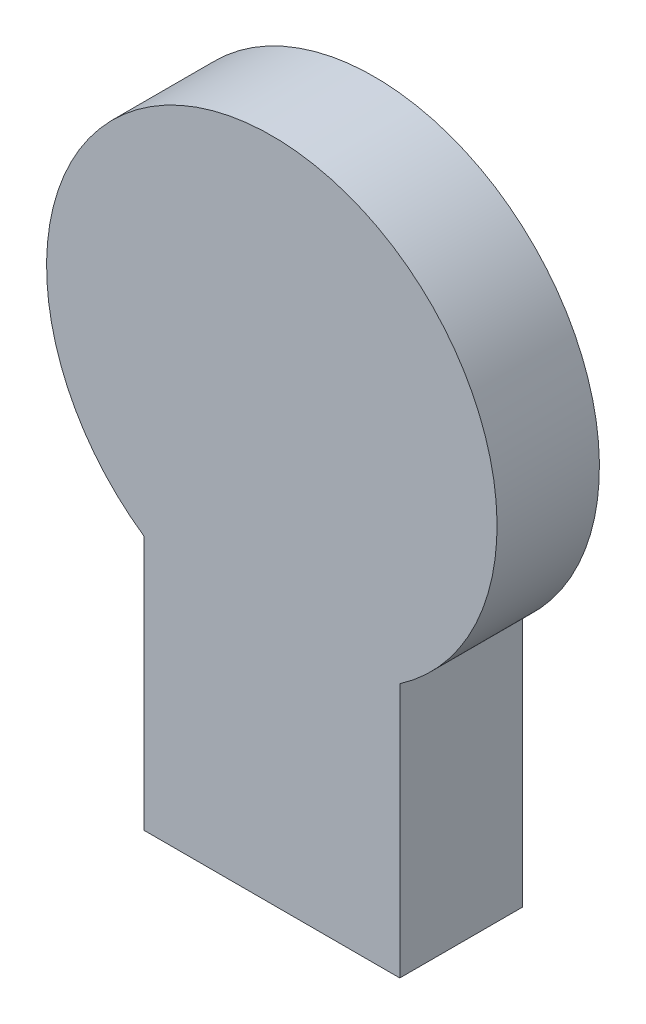
SolidWorks part; units mm, degrees
material "ABS"
ref_plane "Front Plane" through (0, 0, 0) normal (0, 0, 1) x (1, 0, 0)
ref_plane "Top Plane" through (0, 0, 0) normal (0, 1, 0) x (1, 0, 0)
ref_plane "Right Plane" through (0, 0, 0) normal (1, 0, 0) x (0, 0, -1)
sketch "Sketch2" plane through (0, 0, 0) normal (0, 0, 1) x (1, 0, 0)
  line L3 (-25, -36.2077) -> (-25, -86)
  line L4 (-25, -86) -> (25, -86)
  line L5 (25, -86) -> (25, -36.2077)
  arc A2 (-25, -36.2077) -> (25, -36.2077) centre (0, 0) ccw
  circle A3 centre (0, 0) radius 44
extrude "Boss-Extrude1" add sketch "Sketch2" along normal blind 20 contours A2 A3 | A2 L3 L4 L5
sketch "Sketch3" plane through (0, 0, 0) normal (0, 0, -1) x (-1, 0, 0)
  line L0 (-20, -33.4813) -> (-20, -81)
  line L1 (-20, -81) -> (20, -81)
  line L2 (20, -81) -> (20, -33.4813)
  line L3 (-25, -36.2077) -> (-25, -86)
  line L4 (-25, -86) -> (25, -86)
  line L5 (25, -86) -> (25, -36.2077)
  line L6 (-25, -36.2077) -> (-25, -86)
  line L7 (-25, -86) -> (25, -86)
  line L8 (25, -86) -> (25, -36.2077)
  arc A0 (20, -33.4813) -> (-20, -33.4813) centre (0, 0) ccw
  arc A1 (25, -36.2077) -> (-25, -36.2077) centre (0, 0) ccw
  arc A2 (25, -36.2077) -> (-25, -36.2077) centre (0, 0) ccw
  dimension "D1" = 0
  dimension "D2" = 5
extrude "Cut-Extrude1" cut sketch "Sketch3" against normal blind 15 contours A0 L0 L1 L2
sketch "Sketch4" plane through (0, 0, 0) normal (0, 0, -1) x (-1, 0, 0)
  line L0 (-25, -36.2077) -> (-20, -36.2077)
  line L1 (-20, -36.2077) -> (-20, -81)
  line L2 (-20, -33.4813) -> (-20, -81) construction
  line L3 (-25, -36.2077) -> (-25, -86)
  line L4 (-25, -86) -> (25, -86)
  line L5 (25, -86) -> (25, -36.2077)
  line L6 (-25, -36.2077) -> (-25, -86)
  line L7 (-25, -86) -> (25, -86)
  line L8 (25, -86) -> (25, -36.2077)
  line L9 (-20, -81) -> (20, -81)
  line L10 (20, -81) -> (20, -36.2077)
  line L11 (20, -81) -> (20, -33.4813) construction
  line L12 (20, -36.2077) -> (25, -36.2077)
  line L13 (25, -86) -> (25, -36.2077)
  line L14 (25, -86) -> (-25, -86)
  line L15 (-25, -36.2077) -> (-25, -86)
  line L16 (20, -36.2077) -> (25, -36.2077)
  arc A1 (25, -36.2077) -> (-25, -36.2077) centre (0, 0) ccw
  arc A2 (25, -36.2077) -> (-25, -36.2077) centre (0, 0) ccw
  line M6 (20, -33.4813) -> (20, -81)
  line M7 (20, -81) -> (-20, -81)
  line M8 (-20, -81) -> (-20, -33.4813)
  line M10 (-25, -36.2077) -> (-25, -86)
  line M11 (-25, -86) -> (25, -86)
  line M12 (25, -86) -> (25, -36.2077)
  dimension "D1" = 0
extrude "Boss-Extrude2" add sketch "Sketch4" along normal blind 4 contours L12 L0 M6 M7 M8 M10 M11 M12
